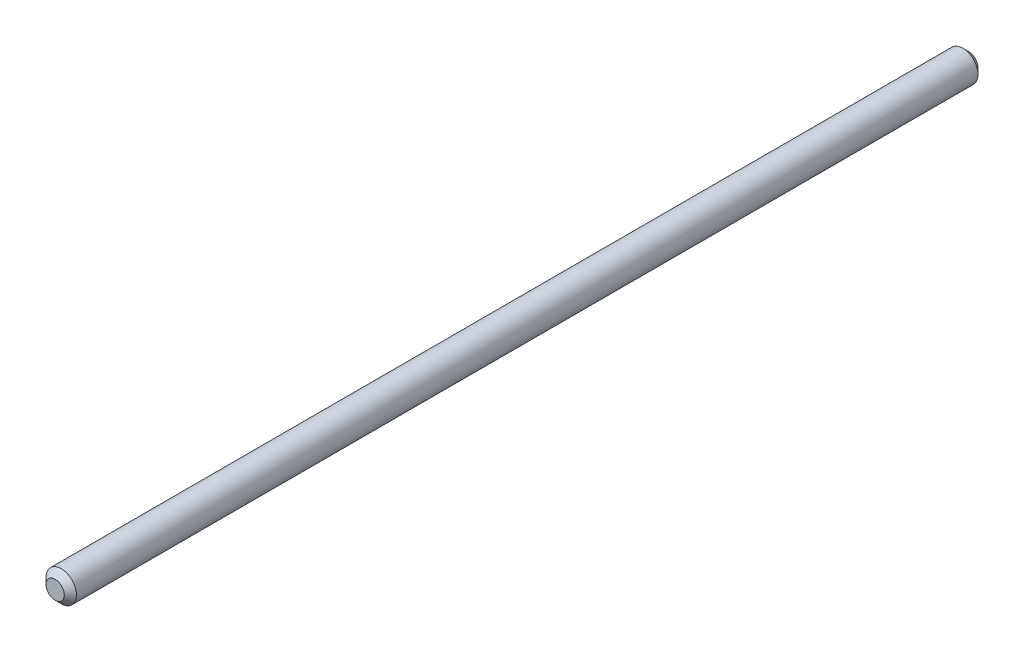
SolidWorks part; units mm, degrees
material "1023 Carbon Steel Sheet (SS)"
ref_plane "Front Plane" through (0, 0, 0) normal (0, 0, 1) x (1, 0, 0)
ref_plane "Top Plane" through (0, 0, 0) normal (0, 1, 0) x (1, 0, 0)
ref_plane "Right Plane" through (0, 0, 0) normal (1, 0, 0) x (0, 0, -1)
sketch "Sketch1" plane through (0, 0, 0) normal (0, 0, 1) x (1, 0, 0)
  circle A0 centre (0, 0) radius 2.5
  dimension "D1" = 5
extrude "Boss-Extrude1" add sketch "Sketch1" along normal blind 150
cosmetic thread "Cosmetic Thread3" parameters "D1"=5, "D2"=4.11
chamfer "Chamfer1" distance 1 angle 45 2 edges at (2.5, 0, 150) (2.5, 0, 0)
equation "\"D1@Sketch1\"=5"
